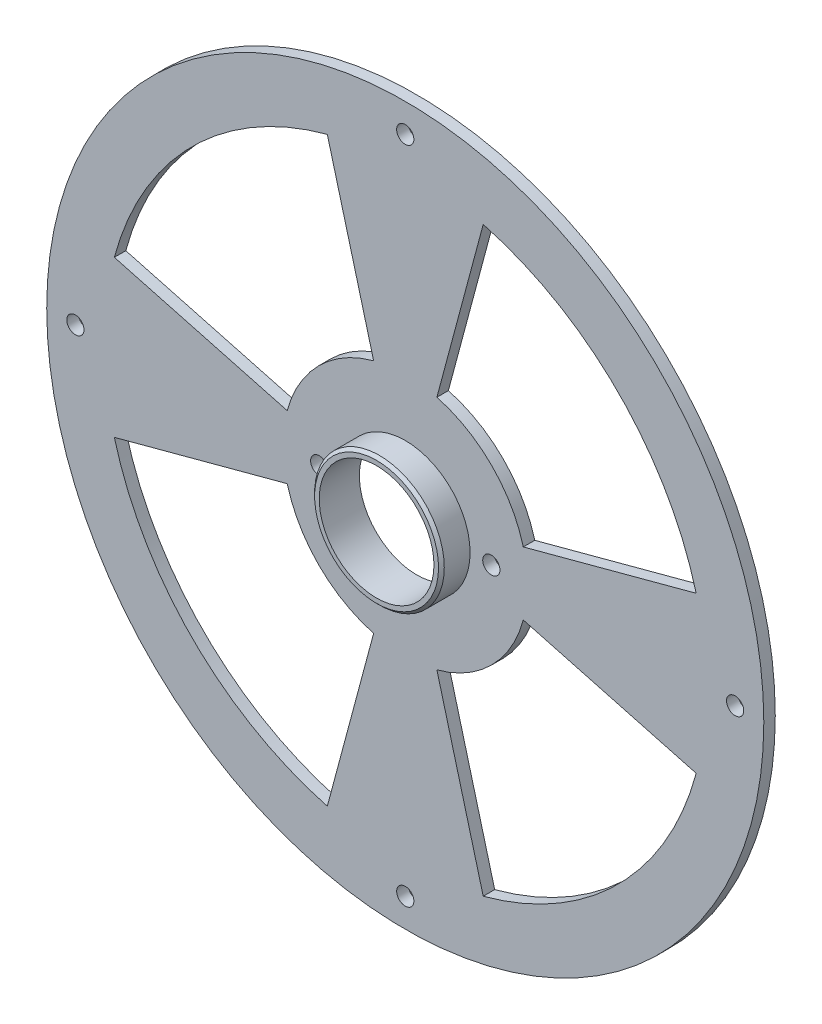
SolidWorks part; units mm, degrees
ref_plane "Front" through (0, 0, 0) normal (0, 0, 1) x (1, 0, 0)
ref_plane "Top" through (0, 0, 0) normal (0, 1, 0) x (1, 0, 0)
ref_plane "Right" through (0, 0, 0) normal (1, 0, 0) x (0, 0, -1)
sketch "Sketch1" plane through (0, 0, 0) normal (0, 0, 1) x (1, 0, 0)
  line L0 (0, 0) -> (-62.5, 0) construction
  line L1 (0, 0) -> (0, -20.2743) construction
  circle A0 centre (0, 0) radius 62.5
  circle A1 centre (-57.5, 0) radius 1.5
  circle A2 centre (0, 57.5) radius 1.5
  circle A3 centre (57.5, 0) radius 1.5
  circle A4 centre (0, -57.5) radius 1.5
  circle A5 centre (-15, 0) radius 1.5
  circle A6 centre (15, 0) radius 1.5
  point P15 (0, 0)
  dimension "D1" = 125
  dimension "D4" = 15
  dimension "D3" = 4
extrude "Boss-Extrude1" add sketch "Sketch1" along normal blind 2
sketch "Sketch2" plane through (0, 0, 2) normal (0, 0, 1) x (1, 0, 0)
  circle A0 centre (0, 0) radius 11.3
extrude "Boss-Extrude2" add sketch "Sketch2" along normal blind 5
sketch "Sector (Cut Extrude)" plane through (0, 0, 2) normal (0, 0, 1) x (1, 0, 0)
  line L0 (0, 0) -> (0, -62.5) construction
  line L1 (62.5, 0) -> (0, 0) construction
  line L2 (20.5742, -5.5128) -> (50.7111, -13.588)
  line L3 (-20.5742, -5.5128) -> (-50.7111, -13.588)
  line L4 (5.5128, -20.5742) -> (13.588, -50.7111)
  line L5 (-5.5128, -20.5742) -> (-13.588, -50.7111)
  line L6 (-5.5128, 20.5742) -> (-13.588, 50.7111)
  line L7 (-20.5742, 5.5128) -> (-50.7111, 13.588)
  line L8 (20.5742, 5.5128) -> (50.7111, 13.588)
  line L9 (5.5128, 20.5742) -> (13.588, 50.7111)
  line L10 (0, 0) -> (50.7111, -13.588) construction
  line L11 (0, 0) -> (13.588, -50.7111) construction
  circle A0 centre (0, 0) radius 62.5 construction
  arc A1 (5.5128, -20.5742) -> (20.5742, -5.5128) centre (0, 0) ccw
  arc A2 (13.588, -50.7111) -> (50.7111, -13.588) centre (0, 0) ccw
  arc A3 (-20.5742, -5.5128) -> (-5.5128, -20.5742) centre (0, 0) ccw
  arc A4 (-50.7111, -13.588) -> (-13.588, -50.7111) centre (0, 0) ccw
  arc A5 (-5.5128, 20.5742) -> (-20.5742, 5.5128) centre (0, 0) ccw
  arc A6 (-13.588, 50.7111) -> (-50.7111, 13.588) centre (0, 0) ccw
  arc A7 (20.5742, 5.5128) -> (5.5128, 20.5742) centre (0, 0) ccw
  arc A8 (50.7111, 13.588) -> (13.588, 50.7111) centre (0, 0) ccw
  circle A9 centre (0, 0) radius 11.3 construction
  point P25 (0, 0)
  dimension "D1" = 4
  dimension "D2" = 10
  dimension "D3" = 10
  dimension "D4" = 15
  dimension "D5" = 15
extrude "Sectors" cut sketch "Sector (Cut Extrude)" against normal through all
sketch "Эскиз1" plane through (0, 0, 7) normal (0, 0, 1) x (1, 0, 0)
  circle A0 centre (0, 0) radius 10
extrude "Вырез-Вытянуть1" cut sketch "Эскиз1" against normal through all
chamfer "Фаска1" distance 0.5 angle 45 1 edges at (11.3, 0, 7)
